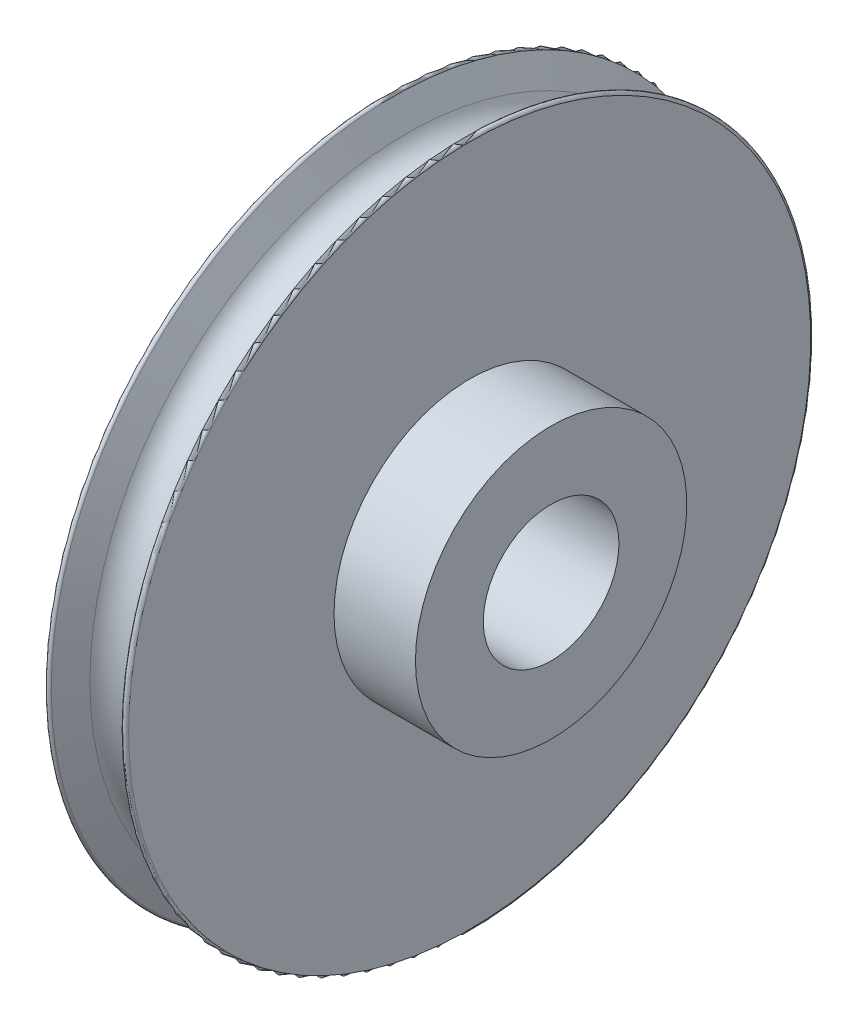
SolidWorks part; units mm, degrees
material "6061-T6 (SS)"
ref_plane "Front Plane" through (0, 0, 0) normal (0, 0, 1) x (1, 0, 0)
ref_plane "Top Plane" through (0, 0, 0) normal (0, 1, 0) x (1, 0, 0)
ref_plane "Right Plane" through (0, 0, 0) normal (1, 0, 0) x (0, 0, -1)
sketch "Sketch1" plane through (0, 0, 0) normal (0, 0, 1) x (1, 0, 0)
  line L0 (-602.9216, 0) -> (29543.159, 0) construction
  line L1 (-601.7144, 17.78) -> (29544.3662, 17.78) construction
  line L2 (0, 17.78) -> (0, -0.2516) construction
  line L3 (-1.905, 0) -> (-1.905, 16.51)
  line L7 (1.905, 0) -> (-1.905, 0)
  line L9 (1.905, 0) -> (1.905, 16.51)
  line L10 (-1.905, 16.51) -> (-1.0702, 14.7976)
  line L11 (1.905, 16.51) -> (1.0702, 14.7976)
  circle A1 centre (0, 15.3194) radius 1.1906 construction
  arc A3 (-1.0702, 14.7976) -> (1.0702, 14.7976) centre (0, 15.3194) ccw
  point P14 (0, 0)
  point P23 (0, 16.51)
  dimension "D3" = 2.3813
  dimension "D4" = 3.81
  dimension "D1" = 17.78
  dimension "D2" = 16.51
revolve "Revolve1" add sketch "Sketch1" angle 360 about L0
fillet "Fillet1" radius 0.127 2 edges at (-1.905, 0, 16.51) (1.905, 0, 16.51)
sketch "Sketch2" plane through (1.905, 0, 0) normal (1, 0, 0) x (0, 0, -1)
  circle A0 centre (0, 0) radius 6.35
  dimension "D1" = 12.7
extrude "Boss-Extrude1" add sketch "Sketch2" along normal blind 3.81
sketch "Sketch3" plane through (5.715, 0, 0) normal (1, 0, 0) x (0, 0, -1)
  circle A0 centre (0, 0) radius 3.175
  dimension "D1" = 6.35
extrude "Cut-Extrude1" cut sketch "Sketch3" against normal through all
